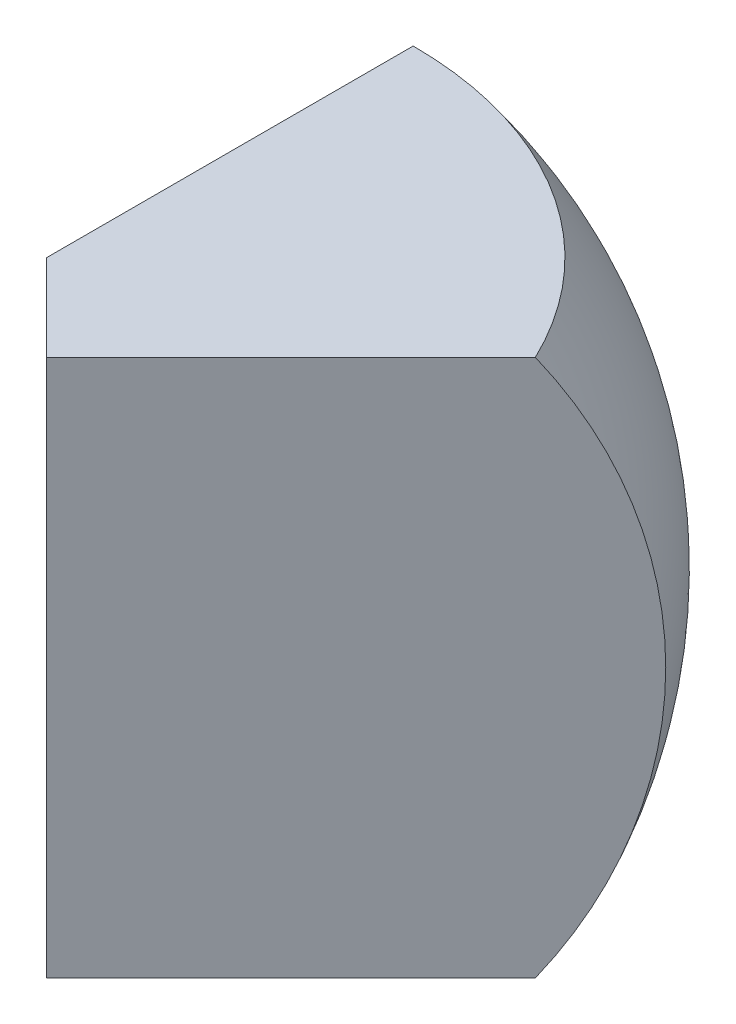
SolidWorks part; units mm, degrees
ref_plane "Płaszczyzna przednia" through (0, 0, 0) normal (0, 0, 1) x (1, 0, 0)
ref_plane "Płaszczyzna górna" through (0, 0, 0) normal (0, 1, 0) x (1, 0, 0)
ref_plane "Płaszczyzna prawa" through (0, 0, 0) normal (1, 0, 0) x (0, 0, -1)
sketch "Szkic1" plane through (0, 0, 0) normal (1, 0, 0) x (0, 0, -1)
  line L0 (0, 0) -> (-111.097, 0) construction
  line L1 (0, -55) -> (0, 55)
  line L2 (0, 55) -> (-75, 55)
  line L3 (0, -55) -> (-75, -55)
  arc A0 (-75, 55) -> (-75, -55) centre (0, 0) ccw
  point P3 (0, 0)
  point P8 (-111.097, 0)
  dimension "D1" = 55
  dimension "D2" = 75
revolve "Obrót1" add sketch "Szkic1" angle 180 about L1
sketch "Szkic2" plane through (0, -55, 0) normal (0, -1, 0) x (1, 0, 0)
  line L0 (0, 0) -> (0, 40)
  line L1 (0, 75) -> (0, -75) construction
  line L2 (0, 40) -> (12.2873, 48.6036)
  line L3 (12.2873, 48.6036) -> (12.2873, 73.9866)
  line L4 (0, 0) -> (17.6777, 17.6777)
  line L5 (17.6777, 17.6777) -> (87.3537, -51.9984)
  line L7 (-26.0659, 75) -> (-26.0659, -104.7585)
  line L8 (-26.0659, -104.7585) -> (87.3537, -104.7585)
  line L9 (87.3537, -104.7585) -> (87.3537, -51.9984)
  line L10 (0, 0) -> (-50.1404, 0)
  line L11 (-50.1404, 0) -> (-50.1404, 112.3931)
  line L12 (-50.1404, 112.3931) -> (99.7171, 112.3931)
  line L13 (99.7171, 112.3931) -> (99.7171, -51.9984)
  line L14 (99.7171, -51.9984) -> (87.3537, -51.9984)
  line L16 (0, 75) -> (-26.0659, 75)
  arc A0 (0, -75) -> (0, 75) centre (0, 0) ccw construction
  arc A1 (67.6777, -32.3223) -> (0, 75) centre (0, 0) ccw
  point P7 (12.2873, 73.9866)
  arc M10 (0, -75) -> (0, 75) centre (0, 0) ccw
  dimension "D1" = 40
  dimension "D2" = 125
  dimension "D3" = 15
  dimension "D4" = 25
  dimension "D5" = 45
extrude "Wytnij-wyciągnięcie6" cut sketch "Szkic2" against normal through all contours L16 L5 L14 L13 L12 L11 L10 L7 M10
sketch "Szkic6" plane through (0, -55, 0) normal (0, -1, 0) x (1, 0, 0)
  line L0 (0, 0) -> (17.6777, 17.6777) construction
  line L1 (0, 75) -> (0, -75)
  line L2 (0, 75) -> (0, 0)
  line L3 (17.6777, 17.6777) -> (87.3537, -51.9984) construction
  line L4 (0, 0) -> (17.6777, 17.6777)
  line L5 (17.6777, 17.6777) -> (87.3537, -51.9984)
  line L6 (0, 0) -> (0, 75)
  arc A2 (0, -75) -> (67.6777, -32.3223) centre (0, 0) ccw
  arc A3 (67.6777, -32.3223) -> (0, 75) centre (0, 0) ccw
  arc A5 (67.6777, -32.3223) -> (0, 75) centre (0, 0) ccw
  arc M5 (67.6777, -32.3223) -> (0, 75) centre (0, 0) ccw
  line M6 (0, 75) -> (0, -75)
  dimension "D1" = 0
extrude "Wytnij-wyciągnięcie7" cut sketch "Szkic6" against normal through all contours L4 L5 M5 M6
